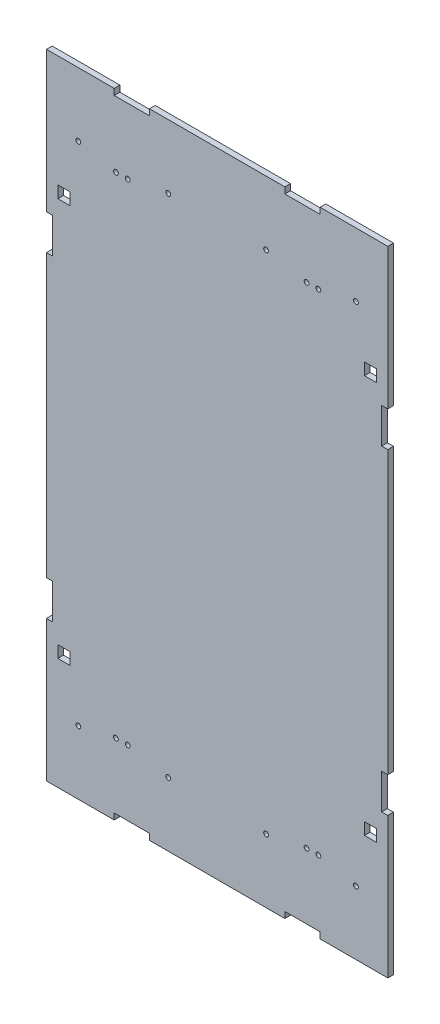
SolidWorks part; units mm, degrees
material "ABS PC"
ref_plane "Front Plane" through (0, 0, 0) normal (0, 0, 1) x (1, 0, 0)
ref_plane "Top Plane" through (0, 0, 0) normal (0, 1, 0) x (1, 0, 0)
ref_plane "Right Plane" through (0, 0, 0) normal (1, 0, 0) x (0, 0, -1)
sketch "Sketch1" plane through (0, 0, 0) normal (0, 0, 1) x (1, 0, 0)
  line L0 (-63.6438, 86.7158) -> (236.3562, 86.7158) construction
  line L1 (-63.6438, 365.2158) -> (236.3562, 365.2158)
  line L2 (-63.6438, 365.2158) -> (-63.6438, -191.7842)
  line L3 (-63.6438, -191.7842) -> (236.3562, -191.7842)
  line L4 (236.3562, 365.2158) -> (236.3562, -191.7842)
  line L6 (231.3562, -186.7842) -> (-58.6438, -186.7842)
  line L7 (231.3562, -186.7842) -> (231.3562, 360.2158)
  line L8 (231.3562, 360.2158) -> (-58.6438, 360.2158)
  line L9 (-58.6438, -186.7842) -> (-58.6438, 360.2158)
  line L10 (231.3562, -186.7842) -> (-58.6438, 360.2158) construction
  line L11 (231.3562, 360.2158) -> (-58.6438, -186.7842) construction
  point P6 (86.3562, 86.7158)
  point P11 (86.3562, 365.2158)
  dimension "D1" = 300
  dimension "D2" = 557
  dimension "D3" = 5
  dimension "D4" = 5
extrude "Boss-Extrude1" add sketch "Sketch1" along normal blind 150
sketch "Sketch2" plane through (0, 0, 150) normal (0, 0, 1) x (1, 0, 0)
  line L5 (236.3562, 365.2158) -> (-63.6438, 365.2158)
  line L6 (236.3562, 365.2158) -> (236.3562, -191.7842)
  line L7 (236.3562, -191.7842) -> (-63.6438, -191.7842)
  line L8 (-63.6438, 365.2158) -> (-63.6438, -191.7842)
extrude "Boss-Extrude2" add sketch "Sketch2" along normal blind 5
sketch "Sketch3" plane through (0, 0, 150) normal (0, 0, -1) x (-1, 0, 0)
  line L1 (-236.3562, -191.7842) -> (-236.3562, 365.2158) construction
  line L11 (-231.3562, -186.7842) -> (-231.3562, 360.2158) construction
  line L12 (58.6438, 86.7158) -> (-231.3562, 86.7158) construction
  line L13 (58.6438, 360.2158) -> (58.6438, -186.7842) construction
  circle A0 centre (-124.3562, 86.7158) radius 10.1
  dimension "D1" = 20.2
  dimension "D2" = 112
extrude "Cut-Extrude1" [suppressed] cut sketch "Sketch3" against normal blind 10
sketch "Sketch4" plane through (0, 0, 155) normal (0, 0, 1) x (1, 0, 0)
  line L2 (187.3293, 107.6808) -> (168.9769, 107.6808)
  line L7 (187.3293, 107.6808) -> (187.3293, 56.8569)
  line L8 (187.3293, 56.8569) -> (168.9769, 56.8569)
  line L9 (168.9769, 107.6808) -> (168.9769, 56.8569)
extrude "Cut-Extrude2" [suppressed] cut sketch "Sketch4" against normal blind 40
sketch "Sketch5" plane through (0, 0, 155) normal (0, 0, 1) x (1, 0, 0)
  line L0 (86.3562, 365.2158) -> (86.3562, -191.7842)
  line L1 (236.3562, 365.2158) -> (-63.6438, 365.2158) construction
  line L2 (-63.6438, -191.7842) -> (236.3562, -191.7842) construction
  line L4 (-2.6438, 302.1015) -> (175.3562, 302.1015) construction
  line L5 (-2.6438, 302.1015) -> (-2.6438, -128.6698) construction
  line L6 (-2.6438, -128.6698) -> (175.3562, -128.6698) construction
  line L7 (175.3562, 302.1015) -> (175.3562, -128.6698) construction
  line L8 (-2.6438, 302.1015) -> (175.3562, -128.6698) construction
  line L9 (-2.6438, -128.6698) -> (175.3562, 302.1015) construction
  circle A0 centre (-2.6438, 302.1015) radius 2.1
  circle A1 centre (-2.6438, -128.6698) radius 2.1
  circle A2 centre (175.3562, -128.6698) radius 2.1
  circle A3 centre (175.3562, 302.1015) radius 2.1
  circle A4 centre (7.7662, 302.1015) radius 2.1
  circle A5 centre (7.7662, -128.6698) radius 2.1
  circle A6 centre (164.9462, -128.6698) radius 2.1
  circle A7 centre (164.9462, 302.1015) radius 2.1
  point P6 (86.3562, 86.7158)
  dimension "D1" = 4.2
  dimension "D2" = 4.2
  dimension "D3" = 4.2
  dimension "D4" = 4.2
  dimension "D5" = 4.2
  dimension "D6" = 178
  dimension "D7" = 10.41
  dimension "D8" = 10.41
  dimension "D9" = 10.41
  dimension "D10" = 10.41
extrude "Cut-Extrude3" cut sketch "Sketch5" against normal blind 10 contours A4 | A0 | A3 | A7 | A1 | A5 | A6 | A2
sketch "Sketch6" plane through (0, 0, 155) normal (0, 0, 1) x (1, 0, 0)
  line L0 (86.3562, 365.2158) -> (86.3562, -191.7842) construction
  line L1 (236.3562, 365.2158) -> (-63.6438, 365.2158) construction
  line L2 (-63.6438, -191.7842) -> (236.3562, -191.7842) construction
  line L3 (236.3562, -191.7842) -> (236.3562, 365.2158) construction
  line L4 (-63.6438, 261.7158) -> (236.3562, 261.7158) construction
  line L5 (-63.6438, 261.7158) -> (-63.6438, -88.2842) construction
  line L6 (-63.6438, -88.2842) -> (236.3562, -88.2842) construction
  line L7 (236.3562, 261.7158) -> (236.3562, -88.2842) construction
  line L8 (-63.6438, 261.7158) -> (236.3562, -88.2842) construction
  line L9 (-63.6438, -88.2842) -> (236.3562, 261.7158) construction
  line L10 (226.3562, 256.4658) -> (215.8562, 266.9658) construction
  line L11 (-53.6438, 266.9658) -> (-43.1438, 266.9658)
  line L12 (-53.6438, 266.9658) -> (-53.6438, 256.4658)
  line L13 (-53.6438, 256.4658) -> (-43.1438, 256.4658)
  line L14 (-43.1438, 266.9658) -> (-43.1438, 256.4658)
  line L15 (-53.6438, 266.9658) -> (-43.1438, 256.4658) construction
  line L16 (-53.6438, 256.4658) -> (-43.1438, 266.9658) construction
  line L17 (226.3562, 266.9658) -> (215.8562, 256.4658) construction
  line L18 (215.8562, 266.9658) -> (215.8562, 256.4658)
  line L19 (226.3562, 256.4658) -> (215.8562, 256.4658)
  line L20 (226.3562, 266.9658) -> (226.3562, 256.4658)
  line L21 (226.3562, 266.9658) -> (215.8562, 266.9658)
  line L22 (-63.6438, 86.7158) -> (86.3562, 86.7158) construction
  line L23 (226.3562, -93.5342) -> (215.8562, -83.0342) construction
  line L24 (226.3562, -83.0342) -> (215.8562, -93.5342) construction
  line L25 (226.3562, -93.5342) -> (215.8562, -93.5342)
  line L26 (226.3562, -93.5342) -> (226.3562, -83.0342)
  line L27 (226.3562, -83.0342) -> (215.8562, -83.0342)
  line L28 (215.8562, -93.5342) -> (215.8562, -83.0342)
  line L29 (-53.6438, -83.0342) -> (-43.1438, -93.5342) construction
  line L30 (-53.6438, -93.5342) -> (-43.1438, -83.0342) construction
  line L31 (-43.1438, -93.5342) -> (-43.1438, -83.0342)
  line L32 (-53.6438, -83.0342) -> (-43.1438, -83.0342)
  line L33 (-53.6438, -93.5342) -> (-53.6438, -83.0342)
  line L34 (-53.6438, -93.5342) -> (-43.1438, -93.5342)
  point P6 (86.3562, 86.7158)
  point P13 (-48.3938, 261.7158)
  point P22 (221.1062, 261.7158)
  point P29 (221.1062, -88.2842)
  point P34 (-48.3938, -88.2842)
  dimension "D1" = 350
  dimension "D2" = 10.5
  dimension "D3" = 10.5
  dimension "D4" = 10
extrude "Cut-Extrude4" cut sketch "Sketch6" against normal blind 10 contours L12 L11 L14 L13 | L31 L32 L33 L34 | L25 L28 L27 L26 | L18 L19 L20 L21
sketch "Sketch7" plane through (236.3562, 0, 0) normal (1, 0, 0) x (0, 0, -1)
  line L0 (-155, 365.2158) -> (0, 365.2158) construction
  line L1 (-3.9103, 365.2158) -> (-14.4103, 365.2158)
  line L2 (-3.9103, 365.2158) -> (-3.9103, 315.2158)
  line L3 (-3.9103, 315.2158) -> (-14.4103, 315.2158)
  line L4 (-14.4103, 365.2158) -> (-14.4103, 315.2158)
  dimension "D1" = 10.5
  dimension "D2" = 50
extrude "Cut-Extrude5" [suppressed] cut sketch "Sketch7" against normal blind 50
sketch "Sketch8" plane through (0, -191.7842, 0) normal (0, -1, 0) x (1, 0, 0)
  line L0 (236.3562, 9.8) -> (-63.6438, 9.8) construction
  line L3 (-63.6438, 0) -> (236.3562, 0) construction
  line L4 (86.3562, 9.8) -> (91.5062, 9.8) construction
  line L5 (86.3562, 9.8) -> (81.2062, 9.8) construction
  circle A0 centre (91.5062, 9.8) radius 1.25
  circle A1 centre (81.2062, 9.8) radius 1.25
  dimension "D4" = 2.5
  dimension "D5" = 2.5
  dimension "D1" = 9.8
  dimension "D2" = 5.15
  dimension "D3" = 5.15
extrude "Cut-Extrude6" cut sketch "Sketch8" against normal blind 663
sketch "Sketch9" plane through (0, 0, 0) normal (0, 0, -1) x (-1, 0, 0)
  line L1 (-236.3562, 365.2158) -> (63.6438, 365.2158)
  line L2 (-236.3562, 365.2158) -> (-236.3562, -191.7842)
  line L3 (-236.3562, -191.7842) -> (63.6438, -191.7842)
  line L4 (63.6438, 365.2158) -> (63.6438, -191.7842)
extrude "Cut-Extrude7" cut sketch "Sketch9" against normal blind 150
sketch "Sketch10" plane through (0, 0, 150) normal (0, 0, -1) x (-1, 0, 0)
  line L0 (-86.3562, -191.7842) -> (-236.3562, -191.7842) construction
  line L1 (-236.3562, -191.7842) -> (63.6438, -191.7842) construction
  line L2 (-86.3562, -191.7842) -> (63.6438, -191.7842) construction
  line L3 (63.6438, -191.7842) -> (63.6438, 365.2158) construction
  line L4 (63.6438, 86.7158) -> (-236.3562, 86.7158) construction
  line L5 (4.1438, -197.1842) -> (-26.8562, -197.1842)
  line L6 (4.1438, -197.1842) -> (4.1438, -186.3842)
  line L7 (4.1438, -186.3842) -> (-26.8562, -186.3842)
  line L8 (-26.8562, -197.1842) -> (-26.8562, -186.3842)
  line L9 (4.1438, -197.1842) -> (-26.8562, -186.3842) construction
  line L10 (4.1438, -186.3842) -> (-26.8562, -197.1842) construction
  line L11 (-145.8562, -197.1842) -> (-176.8562, -197.1842)
  line L12 (-145.8562, -197.1842) -> (-145.8562, -186.3842)
  line L13 (-145.8562, -186.3842) -> (-176.8562, -186.3842)
  line L14 (-176.8562, -197.1842) -> (-176.8562, -186.3842)
  line L15 (-145.8562, -197.1842) -> (-176.8562, -186.3842) construction
  line L16 (-145.8562, -186.3842) -> (-176.8562, -197.1842) construction
  line L17 (-236.3562, 365.2158) -> (-236.3562, -191.7842) construction
  line L18 (-145.8562, 359.8158) -> (-176.8562, 370.6158) construction
  line L19 (-145.8562, 370.6158) -> (-176.8562, 359.8158) construction
  line L20 (4.1438, 359.8158) -> (-26.8562, 370.6158) construction
  line L21 (4.1438, 370.6158) -> (-26.8562, 359.8158) construction
  line L22 (-86.3562, 365.2158) -> (63.6438, 365.2158) construction
  line L23 (-86.3562, 365.2158) -> (-236.3562, 365.2158) construction
  line L24 (-176.8562, 370.6158) -> (-176.8562, 359.8158)
  line L25 (-145.8562, 359.8158) -> (-176.8562, 359.8158)
  line L26 (-145.8562, 370.6158) -> (-145.8562, 359.8158)
  line L27 (-145.8562, 370.6158) -> (-176.8562, 370.6158)
  line L28 (-26.8562, 370.6158) -> (-26.8562, 359.8158)
  line L29 (4.1438, 359.8158) -> (-26.8562, 359.8158)
  line L30 (4.1438, 370.6158) -> (4.1438, 359.8158)
  line L31 (4.1438, 370.6158) -> (-26.8562, 370.6158)
  point P8 (-11.3562, -191.7842)
  point P13 (-161.3562, -191.7842)
  point P33 (-161.3562, 365.2158)
  point P34 (-11.3562, 365.2158)
  dimension "D1" = 31
  dimension "D2" = 31
  dimension "D3" = 10.8
  dimension "D4" = 10.8
extrude "Cut-Extrude8" cut sketch "Sketch10" against normal blind 5
sketch "Sketch11" plane through (0, 0, 150) normal (0, 0, -1) x (-1, 0, 0)
  line L0 (-236.3562, 86.7158) -> (63.6438, 86.7158) construction
  line L1 (-236.3562, 365.2158) -> (-236.3562, -191.7842) construction
  line L2 (63.6438, -191.7842) -> (63.6438, 365.2158) construction
sketch "Sketch12" [suppressed] plane through (0, 0, 155) normal (0, 0, 1) x (1, 0, 0)
  line L0 (134.4562, 86.7158) -> (144.3562, 86.7158) construction
  line L1 (124.3562, 106.7158) -> (124.3562, 66.7158) construction
  line L2 (114.2562, 86.7158) -> (104.3562, 86.7158) construction
  circle A0 centre (124.3562, 86.7158) radius 10.1 construction
  circle A1 centre (124.3562, 86.7158) radius 20 construction
  circle A2 centre (144.3562, 86.7158) radius 2.1
  circle A3 centre (124.3562, 66.7158) radius 2.1
  circle A4 centre (104.3562, 86.7158) radius 2.1
  circle A5 centre (124.3562, 106.7158) radius 2.1
  dimension "D1" = 4.2
  dimension "D2" = 4.2
  dimension "D3" = 4.2
  dimension "D4" = 4.2
extrude "Cut-Extrude9" [suppressed] cut sketch "Sketch12" against normal blind 5
sketch "Sketch13" plane through (0, 0, 150) normal (0, 0, -1) x (-1, 0, 0)
  line L0 (63.6438, 86.7158) -> (63.6438, -191.7842) construction
  line L1 (63.6438, -191.7842) -> (63.6438, 365.2158) construction
  line L2 (63.6438, 86.7158) -> (63.6438, 365.2158) construction
  line L3 (-86.3562, -191.7842) -> (-86.3562, 365.2158) construction
  line L4 (58.2438, -68.0342) -> (69.0438, -68.0342)
  line L5 (58.2438, -68.0342) -> (58.2438, -37.0342)
  line L6 (58.2438, -37.0342) -> (69.0438, -37.0342)
  line L7 (69.0438, -68.0342) -> (69.0438, -37.0342)
  line L8 (58.2438, -68.0342) -> (69.0438, -37.0342) construction
  line L9 (58.2438, -37.0342) -> (69.0438, -68.0342) construction
  line L10 (58.2438, 210.4658) -> (69.0438, 210.4658)
  line L11 (58.2438, 210.4658) -> (58.2438, 241.4658)
  line L12 (58.2438, 241.4658) -> (69.0438, 241.4658)
  line L13 (69.0438, 210.4658) -> (69.0438, 241.4658)
  line L14 (58.2438, 210.4658) -> (69.0438, 241.4658) construction
  line L15 (58.2438, 241.4658) -> (69.0438, 210.4658) construction
  line L16 (-145.8562, -191.7842) -> (-26.8562, -191.7842) construction
  line L17 (-26.8562, 365.2158) -> (-145.8562, 365.2158) construction
  line L18 (-230.9562, 241.4658) -> (-241.7562, 210.4658) construction
  line L19 (-230.9562, 210.4658) -> (-241.7562, 241.4658) construction
  line L20 (-230.9562, -37.0342) -> (-241.7562, -68.0342) construction
  line L21 (-230.9562, -68.0342) -> (-241.7562, -37.0342) construction
  line L22 (-236.3562, 86.7158) -> (-236.3562, 365.2158) construction
  line L23 (-241.7562, 210.4658) -> (-241.7562, 241.4658)
  line L24 (-230.9562, 241.4658) -> (-241.7562, 241.4658)
  line L25 (-230.9562, 210.4658) -> (-230.9562, 241.4658)
  line L26 (-230.9562, 210.4658) -> (-241.7562, 210.4658)
  line L27 (-241.7562, -68.0342) -> (-241.7562, -37.0342)
  line L28 (-230.9562, -37.0342) -> (-241.7562, -37.0342)
  line L29 (-230.9562, -68.0342) -> (-230.9562, -37.0342)
  line L30 (-230.9562, -68.0342) -> (-241.7562, -68.0342)
  point P7 (63.6438, -52.5342)
  point P12 (63.6438, 225.9658)
  point P33 (-236.3562, 225.9658)
  point P34 (-236.3562, -52.5342)
  dimension "D1" = 31
  dimension "D2" = 31
  dimension "D3" = 10.8
  dimension "D4" = 10.8
extrude "Cut-Extrude10" cut sketch "Sketch13" against normal blind 5
sketch "Sketch15" plane through (0, 0, 155) normal (0, 0, 1) x (1, 0, 0)
  line L0 (-60.587, -134.5081) -> (-32.087, -134.5081) construction
  line L2 (-32.087, -134.5081) -> (47.2233, -134.5081) construction
  circle A0 centre (-32.087, -134.5081) radius 2.1
  circle A1 centre (47.2233, -134.5081) radius 2.1
  dimension "D1" = 4.2
  dimension "D3" = 4.2
  dimension "D2" = 28.5
extrude "Cut-Extrude11" [suppressed] cut sketch "Sketch15" against normal blind 10
sketch "Sketch16" plane through (0, 0, 155) normal (0, 0, 1) x (1, 0, 0)
  line L1 (236.3562, 241.4658) -> (236.3562, 365.2158) construction
  line L2 (236.3562, 365.2158) -> (176.8562, 365.2158) construction
  line L3 (86.3562, 365.2158) -> (86.3562, -191.7842) construction
  line L4 (145.8562, 365.2158) -> (26.8562, 365.2158) construction
  line L5 (26.8562, -191.7842) -> (145.8562, -191.7842) construction
  line L6 (236.3562, 86.7158) -> (-63.6438, 86.7158) construction
  line L7 (236.3562, -37.0342) -> (236.3562, 210.4658) construction
  line L8 (-63.6438, 210.4658) -> (-63.6438, -37.0342) construction
  circle A0 centre (208.3562, 309.2158) radius 2.1
  circle A1 centre (129.3564, 309.0364) radius 2.1
  circle A2 centre (43.356, 309.0364) radius 2.1
  circle A3 centre (-35.6438, 309.2158) radius 2.1
  circle A4 centre (-35.6438, -135.7842) radius 2.1
  circle A5 centre (43.356, -135.6047) radius 2.1
  circle A6 centre (129.3564, -135.6047) radius 2.1
  circle A7 centre (208.3562, -135.7842) radius 2.1
  dimension "D1" = 4.2
  dimension "D2" = 4.2
  dimension "D3" = 79
  dimension "D4" = 28
  dimension "D5" = 56
extrude "Cut-Extrude12" cut sketch "Sketch16" against normal blind 10
